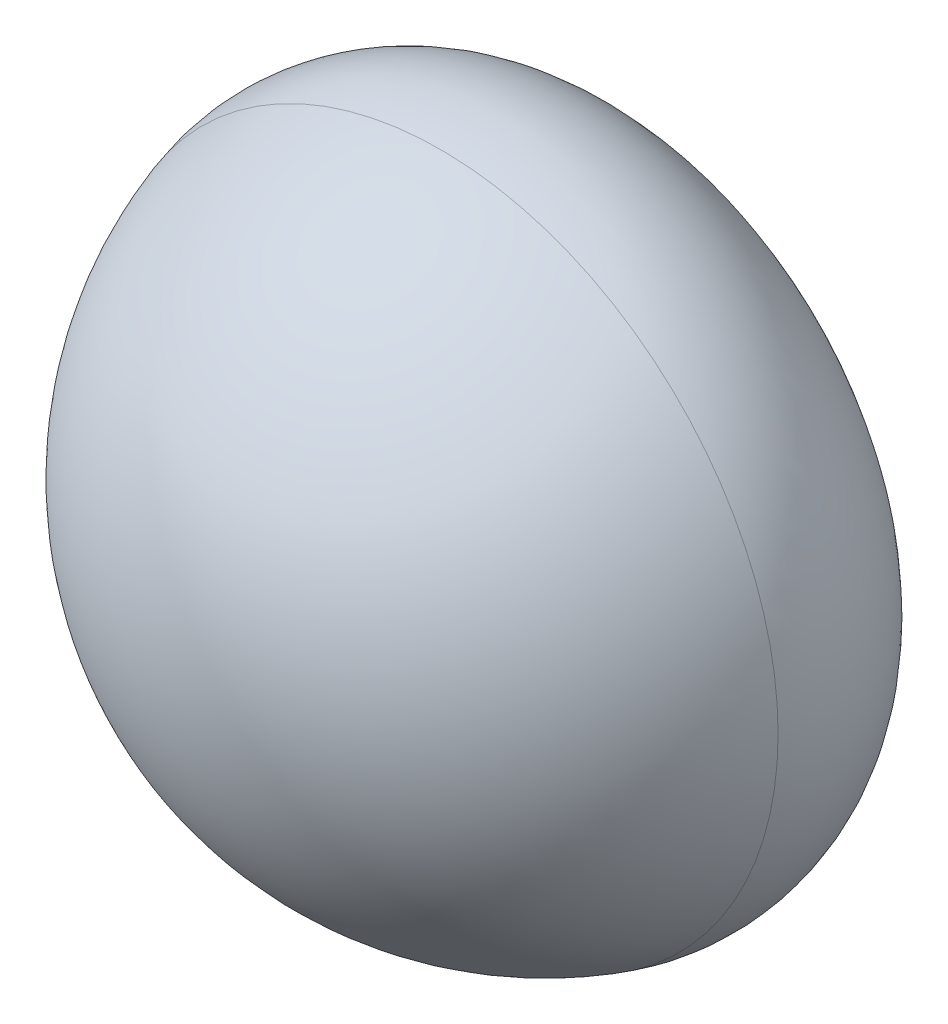
SolidWorks part; units mm, degrees
ref_plane "前视基准面" through (0, 0, 0) normal (0, 0, 1) x (1, 0, 0)
ref_plane "上视基准面" through (0, 0, 0) normal (0, 1, 0) x (1, 0, 0)
ref_plane "右视基准面" through (0, 0, 0) normal (1, 0, 0) x (0, 0, -1)
other "Configuration Table"
sketch "草图2" plane through (0, 0, 0) normal (0, 1, 0) x (1, 0, 0)
  line L0 (0, 0) -> (0, 11.6998) construction
  line L13 (0, -78.8689) -> (0, -86.2689)
  arc A16 (0, -78.8689) -> (3.901, -80.0406) centre (0, -85.9489) cw
  arc A17 (4.8496, -82.7013) -> (0, -86.2689) centre (0, -81.1889) cw
  arc A18 (3.901, -80.0406) -> (4.8496, -82.7013) centre (2.6062, -82.0016) cw
revolve "旋转2" add sketch "草图2" angle 360 about L0
